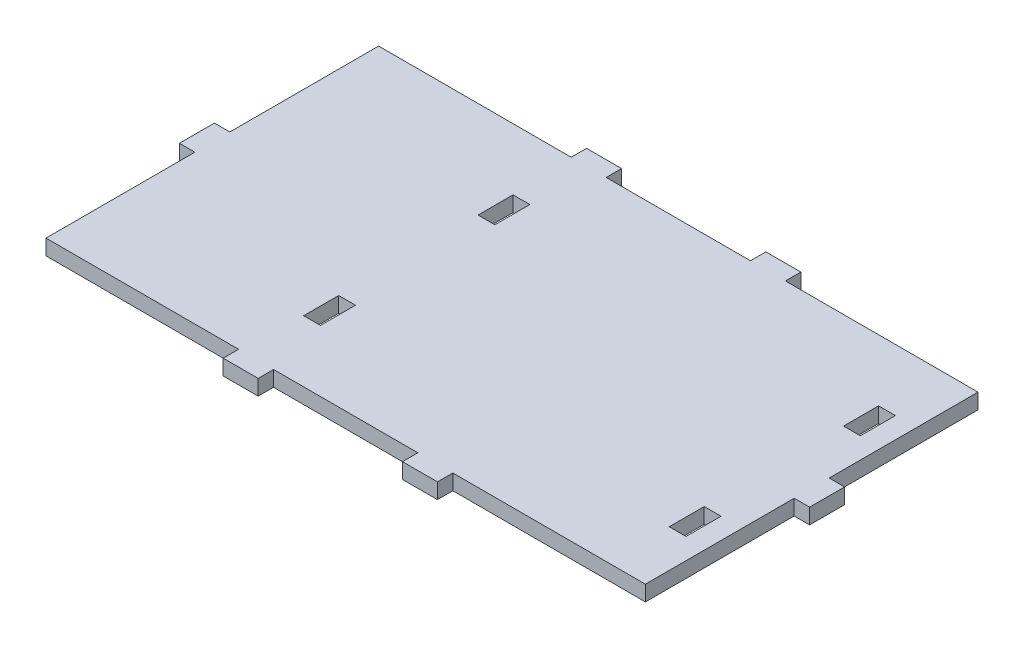
SolidWorks part; units mm, degrees
ref_plane "Front Plane" through (0, 0, 0) normal (0, 0, 1) x (1, 0, 0)
ref_plane "Top Plane" through (0, 0, 0) normal (0, 1, 0) x (1, 0, 0)
ref_plane "Right Plane" through (0, 0, 0) normal (1, 0, 0) x (0, 0, -1)
sketch "Sketch1" plane through (0, 0, 0) normal (0, 1, 0) x (1, 0, 0)
  line L0 (-108.712, 6.35) -> (-114.3, 6.35)
  line L1 (-108.712, -60.325) -> (-38.862, -60.325)
  line L2 (-108.712, -60.325) -> (-108.712, -6.35)
  line L3 (-108.712, 60.325) -> (-38.862, 60.325)
  line L4 (108.712, -60.325) -> (108.712, -6.35)
  line L5 (-108.712, -60.325) -> (108.712, 60.325) construction
  line L6 (-108.712, 60.325) -> (108.712, -60.325) construction
  line L7 (-114.3, 6.35) -> (-114.3, -6.35)
  line L8 (-114.3, -6.35) -> (-108.712, -6.35)
  line L9 (-108.712, 6.35) -> (-108.712, 60.325)
  line L10 (0, 60.325) -> (0, -60.325) construction
  line L11 (114.3, -6.35) -> (108.712, -6.35)
  line L12 (114.3, 6.35) -> (114.3, -6.35)
  line L13 (108.712, 6.35) -> (114.3, 6.35)
  line L14 (108.712, 6.35) -> (108.712, 60.325)
  line L15 (-38.862, 60.325) -> (-38.862, 65.913)
  line L16 (-38.862, 65.913) -> (-26.162, 65.913)
  line L17 (-26.162, 65.913) -> (-26.162, 60.325)
  line L18 (26.162, 60.325) -> (26.162, 65.913)
  line L19 (26.162, 65.913) -> (38.862, 65.913)
  line L20 (38.862, 65.913) -> (38.862, 60.325)
  line L21 (38.862, 60.325) -> (108.712, 60.325)
  line L22 (-26.162, 60.325) -> (26.162, 60.325)
  line L23 (-108.712, 0) -> (106.818, 0) construction
  line L24 (38.862, -65.913) -> (38.862, -60.325)
  line L25 (26.162, -65.913) -> (38.862, -65.913)
  line L26 (26.162, -60.325) -> (26.162, -65.913)
  line L27 (-26.162, -65.913) -> (-26.162, -60.325)
  line L28 (-38.862, -65.913) -> (-26.162, -65.913)
  line L29 (-38.862, -60.325) -> (-38.862, -65.913)
  line L30 (-26.162, -60.325) -> (26.162, -60.325)
  line L31 (38.862, -60.325) -> (108.712, -60.325)
  point P0 (0, 0)
  dimension "D1" = 120.65
  dimension "D2" = 217.424
  dimension "D3" = 12.7
  dimension "D4" = 5.588
  dimension "D5" = 12.7
  dimension "D6" = 5.588
  dimension "D7" = 69.85
extrude "Boss-Extrude1" add sketch "Sketch1" along normal blind 5.588
sketch "Sketch2" plane through (0, 0, 0) normal (0, -1, 0) x (1, 0, 0)
  line L0 (-37.338, 25.4) -> (-37.338, 37.846) construction
  line L1 (-37.592, 25.273) -> (-31.496, 25.273)
  line L2 (-37.592, 25.273) -> (-37.592, 37.973)
  line L3 (-37.592, 37.973) -> (-31.496, 37.973)
  line L4 (-31.496, 25.273) -> (-31.496, 37.973)
  line L5 (-37.592, 25.273) -> (-31.496, 37.973) construction
  line L6 (-37.592, 37.973) -> (-31.496, 25.273) construction
  line L7 (-37.338, 37.846) -> (-31.75, 37.846) construction
  line L8 (94.996, 25.273) -> (101.092, 25.273)
  line L9 (94.996, 25.273) -> (94.996, 37.973)
  line L10 (94.996, 37.973) -> (101.092, 37.973)
  line L11 (101.092, 25.273) -> (101.092, 37.973)
  line L12 (94.996, 25.273) -> (101.092, 37.973) construction
  line L13 (94.996, 37.973) -> (101.092, 25.273) construction
  line L15 (95.25, 25.4) -> (95.25, 37.846) construction
  line L16 (95.25, 25.4) -> (100.838, 25.4) construction
  line L17 (114.3, 0) -> (-114.3, 0) construction
  line L18 (114.3, 6.35) -> (114.3, -6.35) construction
  line L19 (-114.3, -6.35) -> (-114.3, 6.35) construction
  line L20 (94.996, -37.973) -> (101.092, -25.273) construction
  line L21 (94.996, -25.273) -> (101.092, -37.973) construction
  line L22 (-37.592, -37.973) -> (-31.496, -25.273) construction
  line L23 (-37.592, -25.273) -> (-31.496, -37.973) construction
  line L24 (101.092, -25.273) -> (101.092, -37.973)
  line L25 (94.996, -37.973) -> (101.092, -37.973)
  line L26 (94.996, -25.273) -> (94.996, -37.973)
  line L27 (94.996, -25.273) -> (101.092, -25.273)
  line L28 (-31.496, -25.273) -> (-31.496, -37.973)
  line L29 (-37.592, -37.973) -> (-31.496, -37.973)
  line L30 (-37.592, -25.273) -> (-37.592, -37.973)
  line L31 (-37.592, -25.273) -> (-31.496, -25.273)
  point P0 (-34.544, 31.623)
  point P9 (98.044, 31.623)
  point P32 (98.044, -31.623)
  point P33 (-34.544, -31.623)
  dimension "D1" = 6.096
  dimension "D2" = 12.7
  dimension "D3" = 0.254
  dimension "D4" = 0.127
  dimension "D5" = 6.096
  dimension "D6" = 12.7
  dimension "D7" = 0.127
  dimension "D8" = 0.254
extrude "Cut-Extrude1" cut sketch "Sketch2" against normal up to surface (5.588 mm away) up to face at (0, 5.588, 0)
